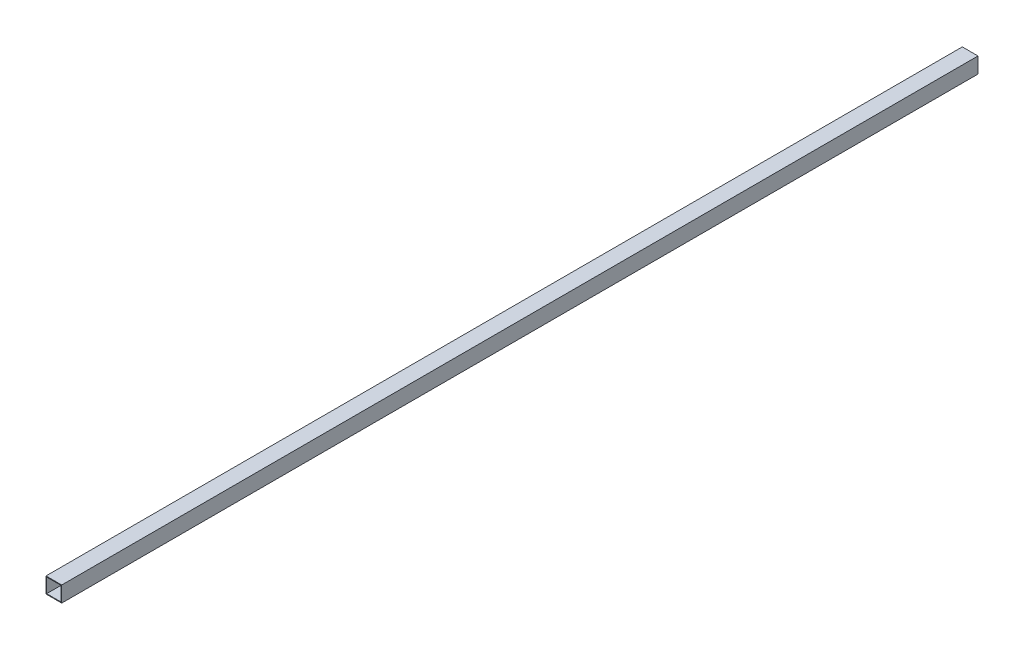
SolidWorks part; units mm, degrees
material "Plain Carbon Steel"
ref_plane "Front Plane" through (0, 0, 0) normal (0, 0, 1) x (1, 0, 0)
ref_plane "Top Plane" through (0, 0, 0) normal (0, 1, 0) x (1, 0, 0)
ref_plane "Right Plane" through (0, 0, 0) normal (1, 0, 0) x (0, 0, -1)
sketch "Sketch2" plane through (0, 0, 0) normal (0, 0, 1) x (1, 0, 0)
  line L0 (0, 19.05) -> (1.5875, 19.05) construction
  line L1 (0, 0) -> (38.1, 0)
  line L2 (0, 0) -> (0, 38.1)
  line L3 (0, 38.1) -> (38.1, 38.1)
  line L4 (38.1, 0) -> (38.1, 38.1)
  line L5 (1.5875, 1.5875) -> (36.5125, 1.5875)
  line L6 (1.5875, 1.5875) -> (1.5875, 36.5125)
  line L7 (1.5875, 36.5125) -> (36.5125, 36.5125)
  line L8 (36.5125, 1.5875) -> (36.5125, 36.5125)
  line L9 (19.05, 36.5125) -> (19.05, 38.1) construction
  line L10 (36.5125, 19.05) -> (38.1, 19.05) construction
  line L11 (19.05, 0) -> (19.05, 1.5875) construction
  dimension "D1" = 38.1
  dimension "D2" = 1.5875
  dimension "D3" = 38.1
extrude "Boss-Extrude1" add sketch "Sketch2" along normal blind 2222.5
